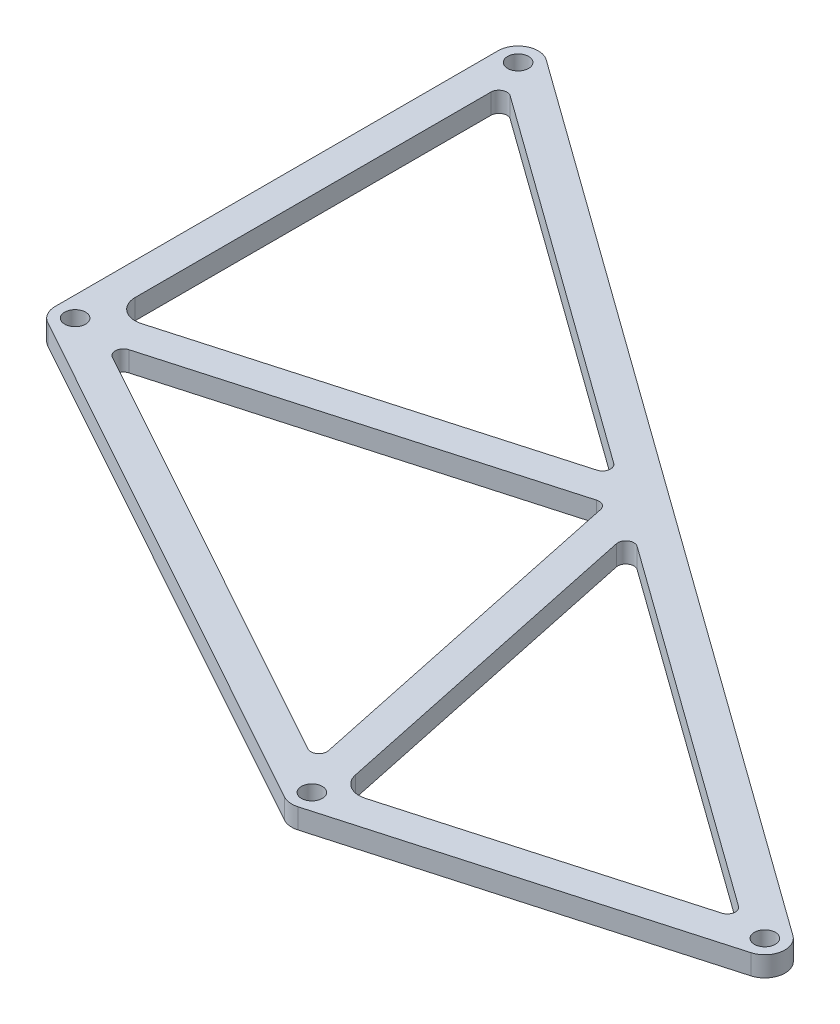
SolidWorks part; units mm, degrees
material "6061-T6 (SS)"
ref_plane "Front Plane" through (0, 0, 0) normal (0, 0, 1) x (1, 0, 0)
ref_plane "Top Plane" through (0, 0, 0) normal (0, 1, 0) x (1, 0, 0)
ref_plane "Right Plane" through (0, 0, 0) normal (1, 0, 0) x (0, 0, -1)
sketch "Sketch3" plane through (0, 0, 0) normal (0, 1, 0) x (-1, 0, 0)
  line L0 (48.3527, -96.9348) -> (326.4889, -297.2527)
  line L3 (336.55, -292.1) -> (336.55, -152.4)
  line L6 (166.416, -54.647) -> (333.271, -146.842)
  line L9 (161.6115, -54.0962) -> (50.3303, -85.6733)
  circle A6 centre (52.0637, -91.7821) radius 3.302
  circle A7 centre (163.3449, -60.205) radius 6.35 construction
  circle A22 centre (52.0637, -91.7821) radius 6.35 construction
  circle A23 centre (330.2, -152.4) radius 6.35 construction
  circle A24 centre (330.2, -292.1) radius 6.35 construction
  circle A25 centre (163.3449, -60.205) radius 3.302
  arc A26 (326.4889, -297.2527) -> (336.55, -292.1) centre (330.2, -292.1) ccw
  arc A27 (333.271, -146.842) -> (336.55, -152.4) centre (330.2, -152.4) cw
  arc A28 (50.3303, -85.6733) -> (48.3527, -96.9348) centre (52.0637, -91.7821) ccw
  arc A29 (161.6115, -54.0962) -> (166.416, -54.647) centre (163.3449, -60.205) cw
  circle A30 centre (330.2, -152.4) radius 3.302
  circle A31 centre (330.2, -292.1) radius 3.302
extrude "Boss-Extrude2" add sketch "Sketch3" along normal blind 6.35
sketch "Sketch9" plane through (0, 6.35, 0) normal (0, 1, 0) x (1, 0, 0)
  line L0 (-330.2, 152.4) -> (-163.3449, 60.205) construction
  line L1 (-163.3449, 60.205) -> (-52.0637, 91.7821) construction
  line L2 (-52.0637, 91.7821) -> (-330.2, 292.1) construction
  line L3 (-330.2, 292.1) -> (-330.2, 152.4) construction
  line L4 (-330.2, 152.4) -> (-191.1319, 191.9411) construction
  line L5 (-191.1319, 191.9411) -> (-163.3449, 60.205) construction
  line L6 (-326.39, 284.6607) -> (-201.3623, 194.6139)
  line L7 (-201.3623, 194.6139) -> (-326.39, 159.0649)
  line L8 (-326.39, 159.0649) -> (-326.39, 284.6607)
  line L9 (-319.0466, 150.5902) -> (-195.6431, 185.6773)
  line L10 (-195.6431, 185.6773) -> (-170.9861, 68.78)
  line L11 (-170.9861, 68.78) -> (-319.0466, 150.5902)
  line L12 (-184.5978, 182.5398) -> (-60.6852, 93.2961)
  line L13 (-60.6852, 93.2961) -> (-159.839, 65.1602)
  line L14 (-159.839, 65.1602) -> (-184.5978, 182.5398)
  line L15 (-48.3527, 96.9348) -> (-326.4889, 297.2527) construction
  line L16 (-336.55, 292.1) -> (-336.55, 152.4) construction
  line L17 (-161.6115, 54.0962) -> (-50.3303, 85.6733) construction
  line L18 (-333.271, 146.842) -> (-166.416, 54.647) construction
  line L19 (-191.1319, 191.9411) -> (-195.6431, 185.6773) construction
  dimension "D1" = 171.3819
  dimension "D2" = 10.16
  dimension "D3" = 10.16
  dimension "D4" = 10.16
  dimension "D5" = 10.16
  dimension "D6" = 10.16
  dimension "D7" = 10.16
  dimension "D8" = 10.16
  dimension "D9" = 14.0692
extrude "Cut-Extrude3" cut sketch "Sketch9" against normal through all contours L7 L8 L6 | L10 L11 L9 | L14 L12 L13
fillet "Fillet2" radius 6.35 1 edges at (-159.839, 3.175, -65.1602)
fillet "Fillet3" radius 2.54 1 edges at (-170.9861, 3.175, -68.78)
fillet "Fillet4" radius 2.54 1 edges at (-319.0466, 3.175, -150.5902)
fillet "Fillet5" radius 6.35 1 edges at (-326.39, 3.175, -159.0649)
fillet "Fillet6" radius 2.54 2 edges at (-60.6852, 3.175, -93.2961) (-326.39, 3.175, -284.6607)
fillet "Fillet7" radius 2.54 3 edges at (-184.5978, 3.175, -182.5398) (-195.6431, 3.175, -185.6773) (-201.3623, 3.175, -194.6139)
